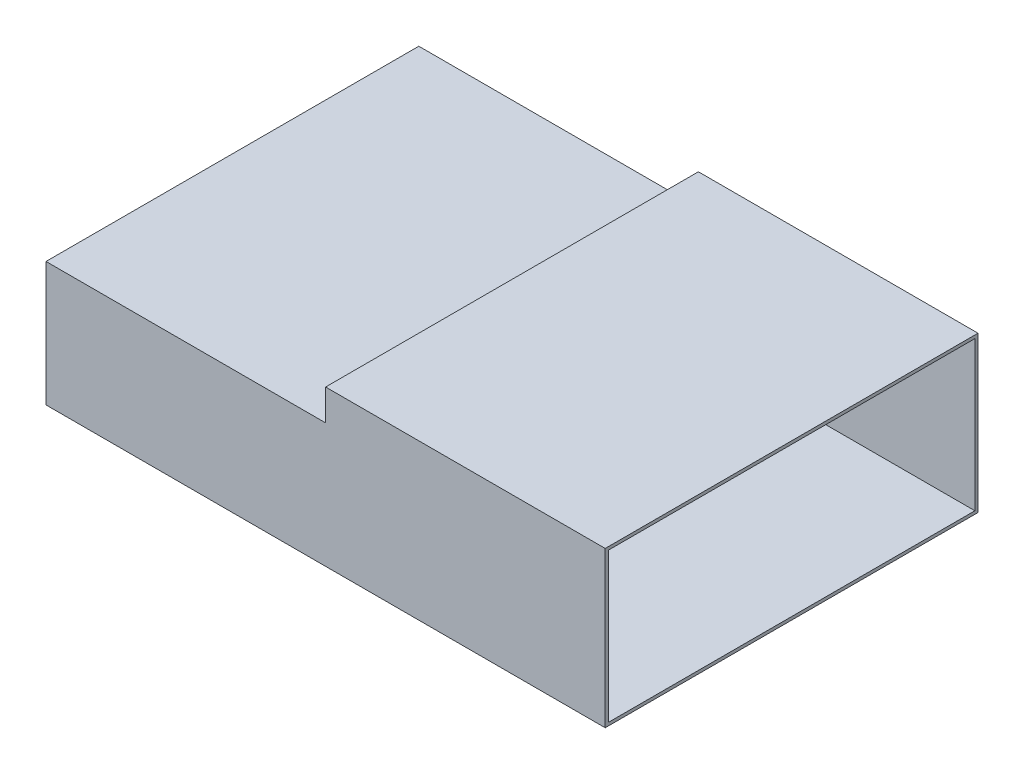
SolidWorks part; units mm, degrees
material "Acrylic (Medium-high impact)"
ref_plane "Front Plane" through (0, 0, 0) normal (0, 0, 1) x (1, 0, 0)
ref_plane "Top Plane" through (0, 0, 0) normal (0, 1, 0) x (1, 0, 0)
ref_plane "Right Plane" through (0, 0, 0) normal (1, 0, 0) x (0, 0, -1)
sketch "Sketch1" plane through (0, 0, 0) normal (0, 1, 0) x (1, 0, 0)
  line L1 (-38.7398, 32.0878) -> (51.2602, 32.0878)
  line L2 (-38.7398, 32.0878) -> (-38.7398, -27.9122)
  line L3 (-38.7398, -27.9122) -> (51.2602, -27.9122)
  line L4 (51.2602, 32.0878) -> (51.2602, -27.9122)
  dimension "D1" = 60
  dimension "D2" = 90
extrude "Boss-Extrude2" add sketch "Sketch1" along normal blind 25
sketch "Sketch2" plane through (0, 0, 0) normal (0, 1, 0) x (1, 0, 0)
  line L0 (-38.7398, -27.9122) -> (51.2602, -27.9122) construction
  line L1 (-38.7398, 32.0878) -> (6.2602, 32.0878)
  line L2 (-38.7398, 32.0878) -> (-38.7398, -27.9122)
  line L3 (-38.7398, -27.9122) -> (6.2602, -27.9122)
  line L4 (6.2602, 32.0878) -> (6.2602, -27.9122)
  dimension "D1" = 45
extrude "Cut-Extrude1" cut sketch "Sketch2" against normal blind 5 from surface at 25 starting at face at (6.2602, 25, -2.0878)
sketch "Sketch4" plane through (51.2602, 0, 0) normal (1, 0, 0) x (0, 0, -1)
  line L0 (-27.9122, 25) -> (32.0878, 25) construction
  line L1 (-27.4122, 24.5) -> (31.5878, 24.5)
  line L2 (-27.4122, 24.5) -> (-27.4122, 0.5)
  line L3 (-27.4122, 0.5) -> (31.5878, 0.5)
  line L4 (31.5878, 24.5) -> (31.5878, 0.5)
  line L5 (-27.9122, 25) -> (-27.9122, 0) construction
  line L6 (-27.9122, 0) -> (32.0878, 0) construction
  line L7 (32.0878, 25) -> (32.0878, 0) construction
  dimension "D1" = 0.5
  dimension "D2" = 0.5
  dimension "D3" = 0.5
  dimension "D4" = 0.5
extrude "Cut-Extrude3" cut sketch "Sketch4" against normal blind 44.5
sketch "Sketch5" plane through (-38.7398, 0, 0) normal (-1, 0, 0) x (0, 0, 1)
  line L0 (-32.0878, 20) -> (-32.0878, 0) construction
  line L1 (-31.5878, 19.5) -> (27.4122, 19.5)
  line L2 (-31.5878, 19.5) -> (-31.5878, 0.5)
  line L3 (-31.5878, 0.5) -> (27.4122, 0.5)
  line L4 (27.4122, 19.5) -> (27.4122, 0.5)
  line L5 (27.9122, 20) -> (27.9122, 0) construction
  line L6 (-32.0878, 20) -> (27.9122, 20) construction
  line L7 (55, 0) -> (-55, 0) construction
  dimension "D1" = 0.5
  dimension "D2" = 0.5
  dimension "D3" = 0.5
  dimension "D4" = 0.5
extrude "Cut-Extrude4" cut sketch "Sketch5" along normal blind 45 from surface at -45.5 starting at face at (6.7602, 12.5, -2.0878)
equation "\"D1@Sketch2\"=85-40"
